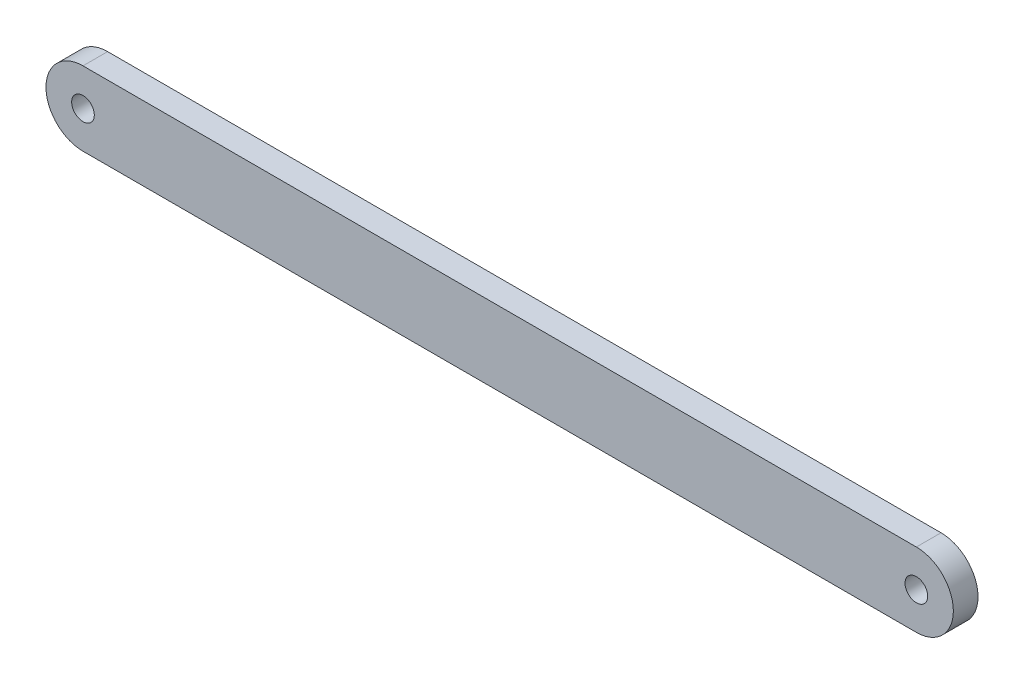
SolidWorks part; units mm, degrees
ref_plane "前视基准面" through (0, 0, 0) normal (0, 0, 1) x (1, 0, 0)
ref_plane "上视基准面" through (0, 0, 0) normal (0, 1, 0) x (1, 0, 0)
ref_plane "右视基准面" through (0, 0, 0) normal (1, 0, 0) x (0, 0, -1)
other "Configuration Table"
sketch "草图1" plane through (0, 0, 0) normal (0, 0, 1) x (1, 0, 0)
  line L1 (-84.5234, 7.5) -> (84.5234, 7.5)
  line L3 (-84.5234, -7.5) -> (84.5234, -7.5)
  line L5 (-84.5234, 7.5) -> (84.5234, -7.5) construction
  line L6 (-84.5234, -7.5) -> (84.5234, 7.5) construction
  arc A0 (-84.5234, 7.5) -> (-84.5234, -7.5) centre (-84.5234, 0) ccw
  arc A1 (84.5234, 7.5) -> (84.5234, -7.5) centre (84.5234, 0) cw
  circle A2 centre (-84.5234, 0) radius 2.3
  circle A3 centre (84.5234, 0) radius 2.3
  point P0 (0, 0)
  dimension "D1" = 4.6
  dimension "D2" = 4.6
  dimension "D3" = 169.0467
  dimension "D4" = 15
extrude "凸台-拉伸1" add sketch "草图1" along normal blind 5
equation "\"fi\"=4.6"
equation "\"D1@草图1\"=\"fi\""
equation "\"D2@草图1\"=\"fi\""
equation "\"b0\"= 75.6'ground"
equation "\"b5\"=(\"b2\"^2+\"b4\"^2)^0.5'斜边"
equation "\"D3@草图1\"=\"b5\""
equation "\"width\"=15"
equation "\"D4@草图1\"=\"width\""
equation "\"depth\"=5"
equation "\"D1@凸台-拉伸1\"=\"depth\""
equation "\"b1\"= \"b0\" *1.4/ 2'rocker"
equation "\"b2\"= \"b0\"'coupler"
equation "\"b3\"= \"b0\" / 2'coupler"
equation "\"b4\"= \"b0\" *2'leg"
equation "\"angle\"= 90度'左右cranker夹角"
